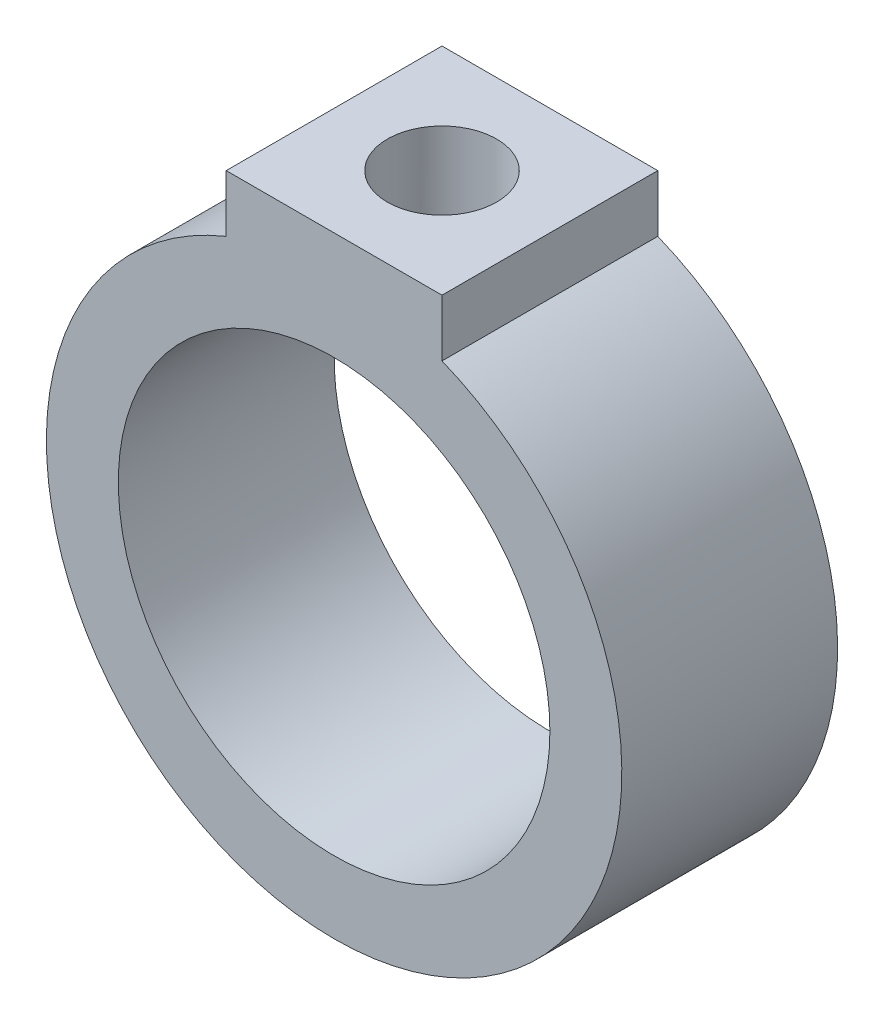
SolidWorks part; units mm, degrees
ref_plane "Front Plane" through (0, 0, 0) normal (0, 0, 1) x (1, 0, 0)
ref_plane "Top Plane" through (0, 0, 0) normal (0, 1, 0) x (1, 0, 0)
ref_plane "Right Plane" through (0, 0, 0) normal (1, 0, 0) x (0, 0, -1)
sketch "Sketch1" plane through (0, 0, 0) normal (0, 0, 1) x (1, 0, 0)
  circle A0 centre (0, 0) radius 25.4
  dimension "D2" = 50.8
extrude "Boss-Extrude1" add sketch "Sketch1" along normal mid plane 19.05
sketch "Sketch2" plane through (0, 0, 0) normal (0, 1, 0) x (1, 0, 0)
  line L1 (-9.525, -9.525) -> (9.525, -9.525)
  line L2 (-9.525, -9.525) -> (-9.525, 9.525)
  line L3 (-9.525, 9.525) -> (9.525, 9.525)
  line L4 (9.525, -9.525) -> (9.525, 9.525)
  line L5 (-9.525, -9.525) -> (9.525, 9.525) construction
  line L6 (-9.525, 9.525) -> (9.525, -9.525) construction
  point P0 (0, 0)
  dimension "D1" = 19.05
  dimension "D2" = 19.05
extrude "Boss-Extrude2" add sketch "Sketch2" along normal blind 28.575
sketch "Sketch3" plane through (0, 0, 9.525) normal (0, 0, 1) x (1, 0, 0)
  line L3 (9.525, 23.5464) -> (9.525, 28.575)
  line L4 (9.525, 28.575) -> (-9.525, 28.575)
  line L5 (-9.525, 28.575) -> (-9.525, 23.5464)
  line L6 (9.525, 23.5464) -> (9.525, 28.575)
  line L7 (9.525, 28.575) -> (-9.525, 28.575)
  line L8 (-9.525, 28.575) -> (-9.525, 23.5464)
  arc A1 (-9.525, 23.5464) -> (9.525, 23.5464) centre (0, 0) ccw
  arc A2 (-9.525, 23.5464) -> (9.525, 23.5464) centre (0, 0) ccw
  circle A3 centre (0, 0) radius 19.05
  dimension "D2" = 38.1
  dimension "D1" = 0
extrude "Cut-Extrude1" cut sketch "Sketch3" against normal through all contours A3
sketch "Sketch4" plane through (0, 28.575, 0) normal (0, 1, 0) x (1, 0, 0)
  line L4 (9.525, -9.525) -> (9.525, 9.525)
  line L5 (9.525, 9.525) -> (-9.525, 9.525)
  line L6 (-9.525, 9.525) -> (-9.525, -9.525)
  line L7 (-9.525, -9.525) -> (9.525, -9.525)
  line L8 (9.525, -9.525) -> (9.525, 9.525)
  line L9 (9.525, 9.525) -> (-9.525, 9.525)
  line L10 (-9.525, 9.525) -> (-9.525, -9.525)
  line L11 (-9.525, -9.525) -> (9.525, -9.525)
  circle A0 centre (0, 0) radius 4.826
  point P6 (0, 0)
  dimension "D2" = 9.652
  dimension "D1" = 0
extrude "Cut-Extrude2" cut sketch "Sketch4" against normal up to surface (9.525 mm away) contours A0
